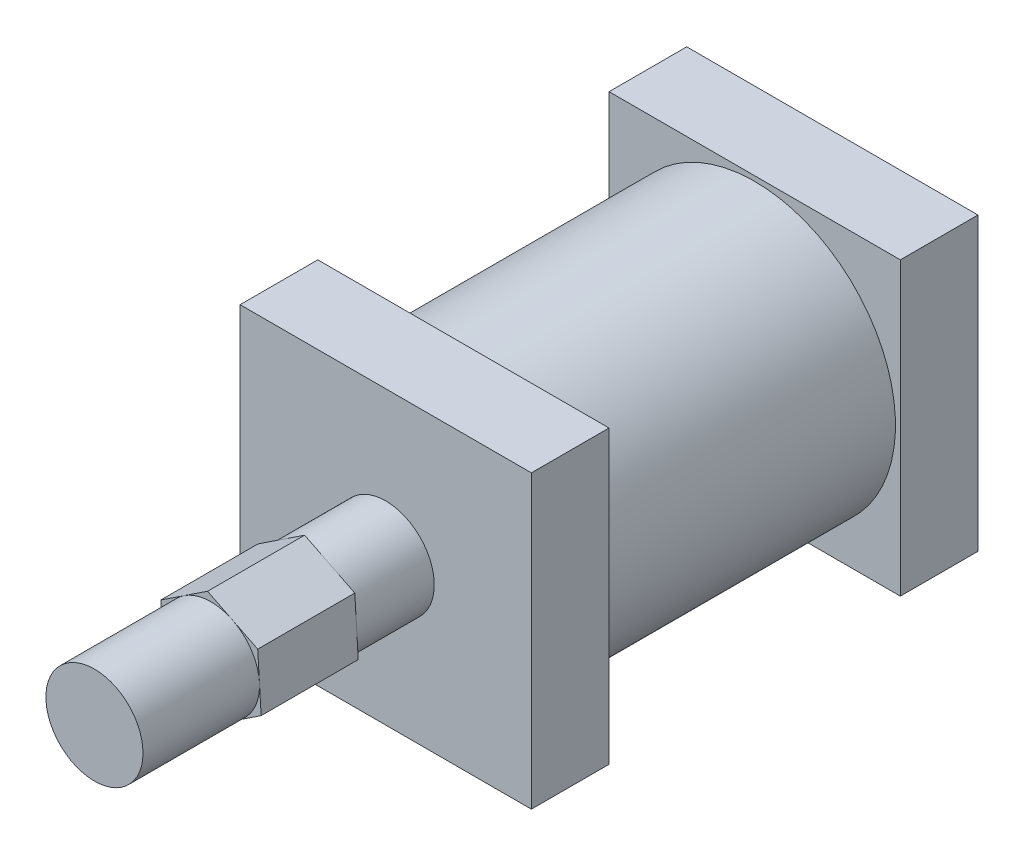
SolidWorks part; units mm, degrees
ref_plane "Front Plane" through (0, 0, 0) normal (0, 0, 1) x (1, 0, 0)
ref_plane "Top Plane" through (0, 0, 0) normal (0, 1, 0) x (1, 0, 0)
ref_plane "Right Plane" through (0, 0, 0) normal (1, 0, 0) x (0, 0, -1)
sketch "Sketch1" plane through (0, 0, 0) normal (0, 0, 1) x (1, 0, 0)
  line L1 (0, 0) -> (38.1, 0)
  line L2 (0, 0) -> (0, 38.1)
  line L3 (0, 38.1) -> (38.1, 38.1)
  line L4 (38.1, 0) -> (38.1, 38.1)
  dimension "D1" = 38.1
  dimension "D2" = 38.1
extrude "Boss-Extrude1" add sketch "Sketch1" along normal blind 10.16
sketch "Sketch2" plane through (0, 0, 10.16) normal (0, 0, 1) x (1, 0, 0)
  line L0 (0, 38.1) -> (0, 0) construction
  line L1 (38.1, 38.1) -> (0, 38.1) construction
  circle A0 centre (19.05, 19.05) radius 18.415
  dimension "D3" = 36.83
  dimension "D1" = 19.05
  dimension "D2" = 19.05
extrude "Boss-Extrude2" add sketch "Sketch2" along normal blind 38.1
sketch "Sketch3" plane through (0, 0, 48.26) normal (0, 0, 1) x (1, 0, 0)
  line L1 (0, 0) -> (38.1, 0)
  line L2 (0, 0) -> (0, 38.1)
  line L3 (0, 38.1) -> (38.1, 38.1)
  line L4 (38.1, 0) -> (38.1, 38.1)
extrude "Boss-Extrude3" add sketch "Sketch3" along normal blind 10.16
sketch "Sketch4" plane through (0, 0, 58.42) normal (0, 0, 1) x (1, 0, 0)
  line L0 (38.1, 0) -> (38.1, 38.1) construction
  line L1 (0, 0) -> (38.1, 0) construction
  circle A0 centre (19.05, 19.05) radius 6.35
  dimension "D1" = 12.7
  dimension "D2" = 19.05
  dimension "D3" = 19.05
extrude "Boss-Extrude4" add sketch "Sketch4" along normal blind 10.16
sketch "Sketch5" plane through (0, 0, 68.58) normal (0, 0, 1) x (1, 0, 0)
  line L1 (25.1641, 23.0974) -> (18.6019, 26.3686)
  line L2 (18.6019, 26.3686) -> (12.4878, 22.3213)
  line L3 (12.4878, 22.3213) -> (12.9359, 15.0026)
  line L4 (12.9359, 15.0026) -> (19.4981, 11.7314)
  line L5 (19.4981, 11.7314) -> (25.6122, 15.7787)
  line L6 (25.6122, 15.7787) -> (25.1641, 23.0974)
  circle A0 centre (19.05, 19.05) radius 6.35 construction
extrude "Boss-Extrude5" add sketch "Sketch5" along normal blind 12.7
sketch "Sketch6" plane through (0, 0, 81.28) normal (0, 0, 1) x (1, 0, 0)
  line L0 (0, 38.1) -> (0, 0) construction
  line L1 (0, 0) -> (38.1, 0) construction
  circle A0 centre (19.05, 19.05) radius 6.35
  dimension "D1" = 12.7
  dimension "D2" = 19.05
  dimension "D3" = 19.05
extrude "Boss-Extrude6" add sketch "Sketch6" along normal blind 15.24
